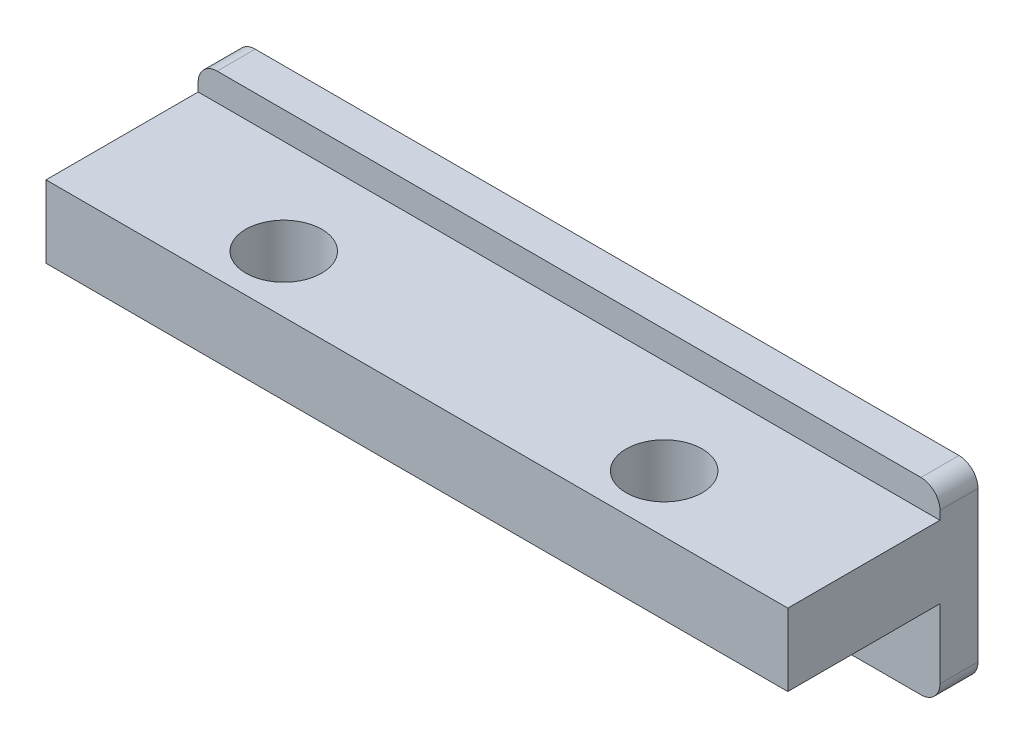
SolidWorks part; units mm, degrees
ref_plane "Plan de face" through (0, 0, 0) normal (0, 0, 1) x (1, 0, 0)
ref_plane "Plan de dessus" through (0, 0, 0) normal (0, 1, 0) x (1, 0, 0)
ref_plane "Plan de droite" through (0, 0, 0) normal (1, 0, 0) x (0, 0, -1)
sketch "Esquisse1" plane through (0, 0, 0) normal (0, 0, 1) x (1, 0, 0)
  line L0 (-2.8893, -3) -> (43.5076, -3) construction
  line L1 (0, 0) -> (39, 0) construction
  line L2 (0, 0) -> (0, 6.9)
  line L3 (0, 6.9) -> (39, 6.9)
  line L4 (39, 0) -> (39, 6.9)
  line L5 (10, -5.3372) -> (10, 1.8096) construction
  line L6 (29, -5.3372) -> (29, 1.8096) construction
  line L7 (0, 0) -> (0, -3)
  line L8 (0, -3) -> (10, -3)
  line L9 (10, -3) -> (10, 0)
  line L10 (10, 0) -> (29, 0)
  line L11 (29, 0) -> (29, -3)
  line L12 (29, -3) -> (39, -3)
  line L13 (39, -3) -> (39, 0)
  dimension "D1" = 39
  dimension "D2" = 6.9
  dimension "D3" = 3
  dimension "D4" = 10
  dimension "D5" = 10
extrude "Boss.-Extru.1" add sketch "Esquisse1" along normal blind 2
sketch "Esquisse2" plane through (0, 0, 2) normal (0, 0, 1) x (1, 0, 0)
  line L0 (39, -3) -> (39, 6.9) construction
  line L1 (0, 6.9) -> (39, 6.9) construction
  line L2 (0, 6.9) -> (0, 5.45) construction
  line L3 (0, 5.45) -> (39, 5.45) construction
  line L4 (39, 6.9) -> (39, 5.45) construction
  line L6 (39, 1.65) -> (0, 1.65) construction
  line L7 (39, 1.65) -> (39, 0) construction
  line L8 (39, 0) -> (0, 0) construction
  line L9 (0, 1.65) -> (0, 0) construction
  line L10 (39, 5.45) -> (0, 5.45)
  line L11 (39, 5.45) -> (39, 1.65)
  line L12 (39, 1.65) -> (0, 1.65)
  line L13 (0, 5.45) -> (0, 1.65)
  dimension "D1" = 3.8
  dimension "D2" = 1.45
extrude "Boss.-Extru.2" add sketch "Esquisse2" along normal blind 8
sketch "Esquisse3" plane through (0, 1.65, 0) normal (0, 1, 0) x (1, 0, 0)
  line L0 (0, -2) -> (39, -2) construction
  line L1 (39, -10) -> (0, -10) construction
  line L3 (19.5, 0) -> (19.5, -31.4409) construction
  line L5 (29.5, -7) -> (9.5, -7) construction
  circle A0 centre (9.5, -7) radius 2
  circle A1 centre (29.5, -7) radius 2
  point P0 (19.5, -7)
  point P1 (19.5, -10)
  point P8 (0, 0)
  point P13 (0, 0)
  dimension "D1" = 4
  dimension "D2" = 4
  dimension "D3" = 20
  dimension "D4" = 5
extrude "Enlèv. mat.-Extru.1" cut sketch "Esquisse3" against normal through all and the other way through all
fillet "Congé1" radius 1 8 edges at (39, 6.9, 1) (0, 6.9, 1) (0, -3, 1) (10, -3, 1) (10, 0, 1) (39, -3, 1) (29, -3, 1) (29, 0, 1)
